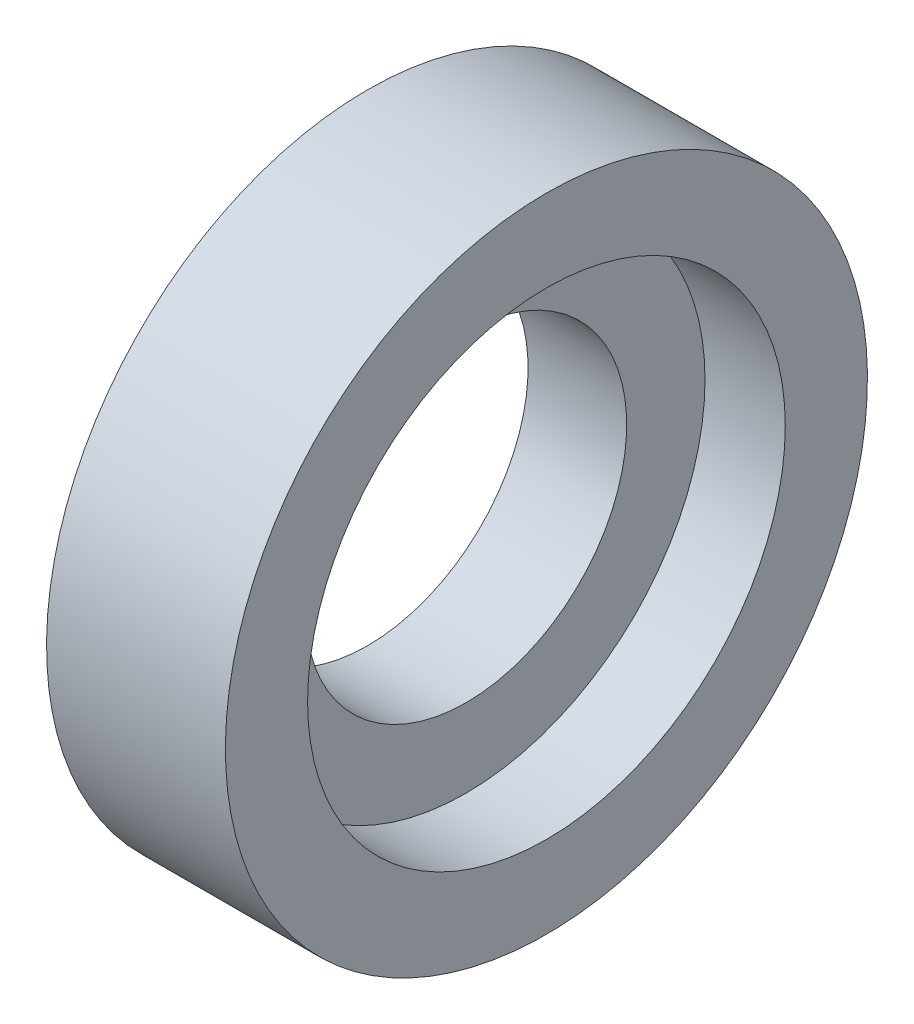
SolidWorks part; units mm, degrees
ref_plane "Front Plane" through (0, 0, 0) normal (0, 0, 1) x (1, 0, 0)
ref_plane "Top Plane" through (0, 0, 0) normal (0, 1, 0) x (1, 0, 0)
ref_plane "Right Plane" through (0, 0, 0) normal (1, 0, 0) x (0, 0, -1)
sketch "Sketch1" plane through (0, 0, 0) normal (0, 0, 1) x (1, 0, 0)
  line L0 (0, 0) -> (0, 9.4488)
  line L2 (3.9014, 9.4488) -> (3.9014, 6.35)
  line L3 (3.9014, 6.35) -> (3.9014, 0)
  line L4 (3.9014, 0) -> (0, 0)
  line L5 (3.9014, 6.35) -> (0, 6.35)
  line L6 (0, 9.4488) -> (0, 12.7)
  line L7 (0, 12.7) -> (7.0764, 12.7)
  line L8 (7.0764, 12.7) -> (7.0764, 9.4488)
  line L9 (7.0764, 9.4488) -> (3.9014, 9.4488)
  dimension "D1" = 3.9014
  dimension "D2" = 9.4488
  dimension "D3" = 6.35
  dimension "D4" = 12.7
  dimension "D5" = 7.0764
  dimension "D6" = 3.0988
revolve "Revolve1" add sketch "Sketch1" angle 360 about L4
